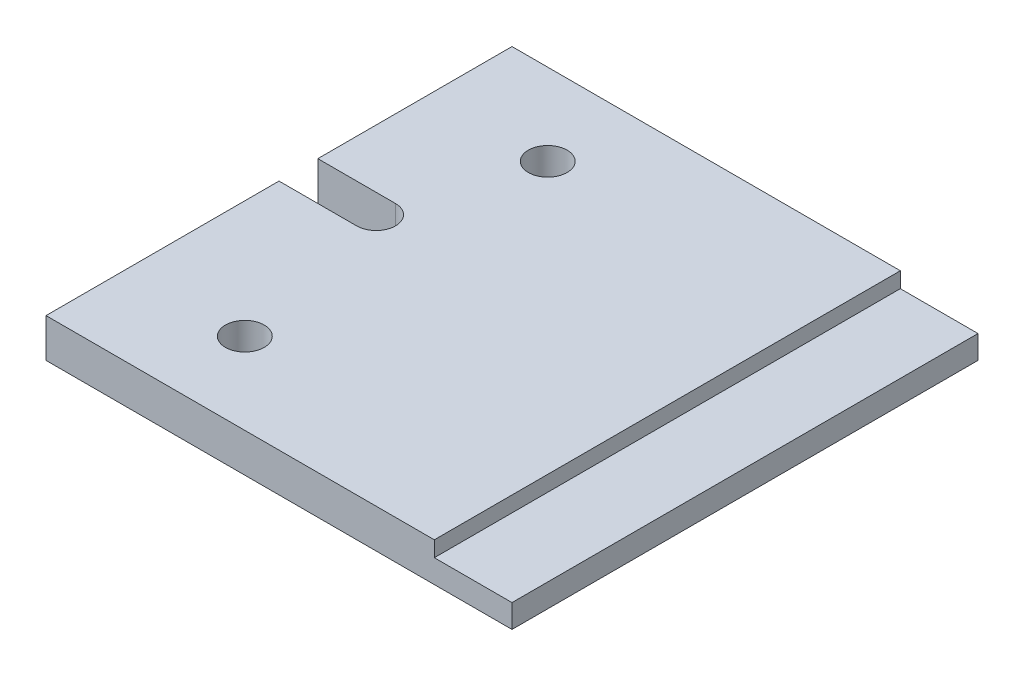
SolidWorks part; units mm, degrees
material "6061-T6 (SS)"
ref_plane "X-Y Datum" through (0, 0, 0) normal (0, 0, 1) x (1, 0, 0)
ref_plane "X-Z Datum" through (0, 0, 0) normal (0, 1, 0) x (1, 0, 0)
ref_plane "Y-Z Datum" through (0, 0, 0) normal (1, 0, 0) x (0, 0, -1)
sketch "Sketch1" plane through (0, 0, 0) normal (0, 1, 0) x (1, 0, 0)
  line L0 (0, 38.1) -> (76.2, 38.1) construction
  line L1 (0, 0) -> (76.2, 0)
  line L2 (0, 0) -> (0, 76.2)
  line L3 (0, 76.2) -> (76.2, 76.2)
  line L4 (76.2, 0) -> (76.2, 76.2)
  line L6 (76.2, 0) -> (63.5, 0)
  line L7 (76.2, 0) -> (76.2, 76.2)
  line L8 (76.2, 76.2) -> (63.5, 76.2)
  line L9 (63.5, 0) -> (63.5, 76.2)
  circle A0 centre (19.177, 13.335) radius 3.175
  circle A2 centre (19.177, 62.865) radius 3.175
  dimension "D5" = 6.35
  dimension "D1" = 76.2
  dimension "D2" = 76.2
  dimension "D3" = 19.177
  dimension "D4" = 13.335
  dimension "D6" = 12.7
extrude "Boss-Extrude1" add sketch "Sketch1" along normal blind 6.35 contours A2 | L2 L0 L9 L3 A2 | L9 L0 L7 L3 | L0 L9 L1 L4 | L0 L2 L1 L9 A0
sketch "Sketch2" plane through (0, 6.35, 0) normal (0, 1, 0) x (1, 0, 0)
  line L0 (76.2, 0) -> (76.2, 76.2) construction
  line L1 (63.5, 0) -> (63.5, 76.2) construction
  line L2 (76.2, 0) -> (76.2, 76.2)
  line L3 (63.5, 0) -> (63.5, 76.2)
  line L4 (63.5, 76.2) -> (76.2, 76.2)
  line L5 (63.5, 0) -> (76.2, 0)
extrude "Cut-Extrude1" cut sketch "Sketch2" against normal blind 2.54
sketch "Sketch3" plane through (0, 6.35, 0) normal (0, 1, 0) x (1, 0, 0)
  line L0 (0, 0) -> (0, 76.2) construction
  line L1 (0, 44.45) -> (12.7, 44.45)
  line L2 (0, 44.45) -> (0, 38.1)
  line L3 (0, 38.1) -> (12.7, 38.1)
  line L5 (0, 0) -> (63.5, 0) construction
  arc A0 (12.7, 44.45) -> (12.7, 38.1) centre (12.7, 41.275) cw
  dimension "D1" = 3.175
  dimension "D2" = 12.7
  dimension "D3" = 38.1
extrude "Cut-Extrude2" cut sketch "Sketch3" against normal through all
